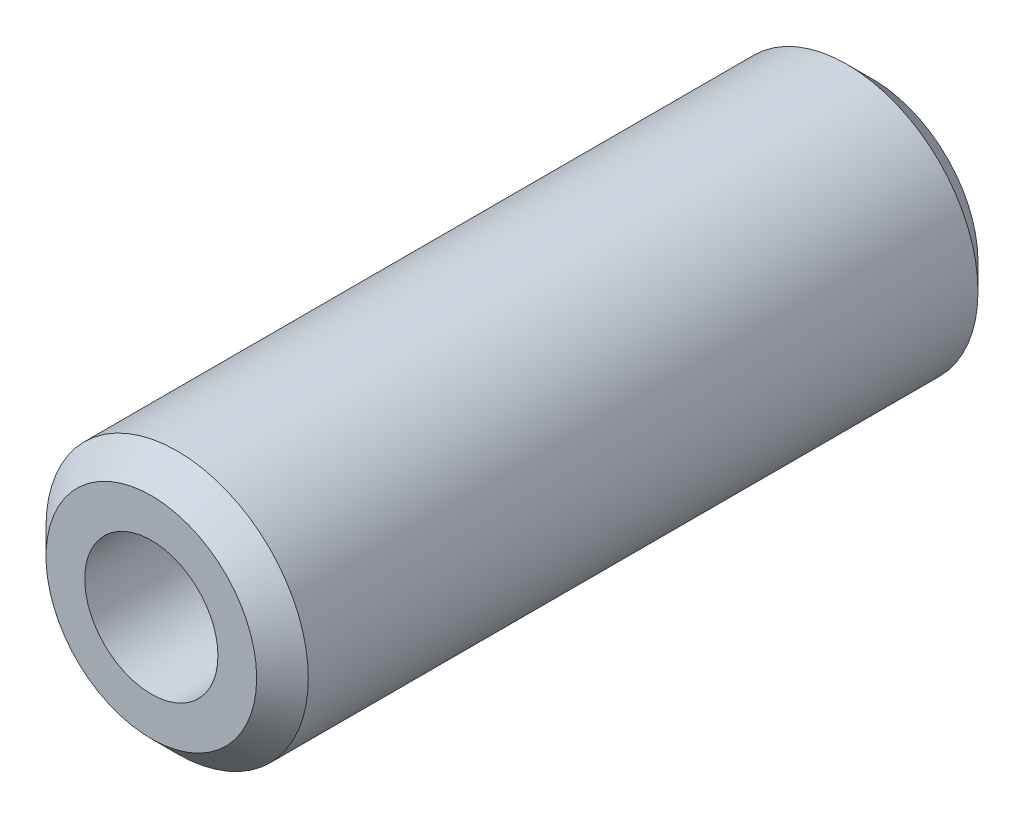
SolidWorks part; units mm, degrees
material "Alloy Steel"
ref_plane "Front Plane" through (0, 0, 0) normal (0, 0, 1) x (1, 0, 0)
ref_plane "Top Plane" through (0, 0, 0) normal (0, 1, 0) x (1, 0, 0)
ref_plane "Right Plane" through (0, 0, 0) normal (1, 0, 0) x (0, 0, -1)
sketch "Sketch1" plane through (0, 0, 0) normal (0, 0, 1) x (1, 0, 0)
  circle A0 centre (0, 0) radius 12.7
  dimension "D1" = 25.4
extrude "Boss-Extrude1" add sketch "Sketch1" along normal mid plane 69.85
sketch "Sketch2" plane through (0, 0, 34.925) normal (0, 0, 1) x (1, 0, 0)
  circle A0 centre (0, 0) radius 6.45
  dimension "D1" = 12.9
extrude "Cut-Extrude1" cut sketch "Sketch2" against normal through all
chamfer "Chamfer1" distance 2.5 2 edges at (12.7, 0, -34.925) (12.7, 0, 34.925)
